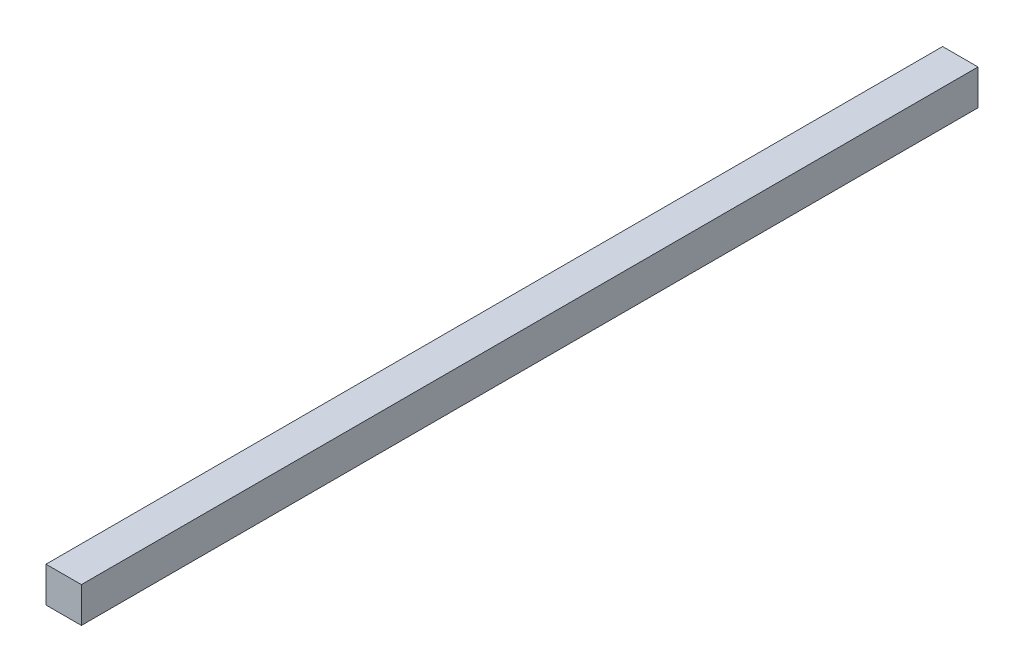
SolidWorks part; units mm, degrees
ref_plane "Front Plane" through (0, 0, 0) normal (0, 0, 1) x (1, 0, 0)
ref_plane "Top Plane" through (0, 0, 0) normal (0, 1, 0) x (1, 0, 0)
ref_plane "Right Plane" through (0, 0, 0) normal (1, 0, 0) x (0, 0, -1)
sketch "Sketch1" plane through (0, 0, 0) normal (1, 0, 0) x (0, 0, -1)
  line L1 (0, 0) -> (456, 0)
  line L2 (0, 0) -> (0, 18)
  line L3 (0, 18) -> (456, 18)
  line L4 (456, 0) -> (456, 18)
  dimension "D1" = 456
  dimension "D2" = 18
extrude "Boss-Extrude1" add sketch "Sketch1" along normal blind 18
